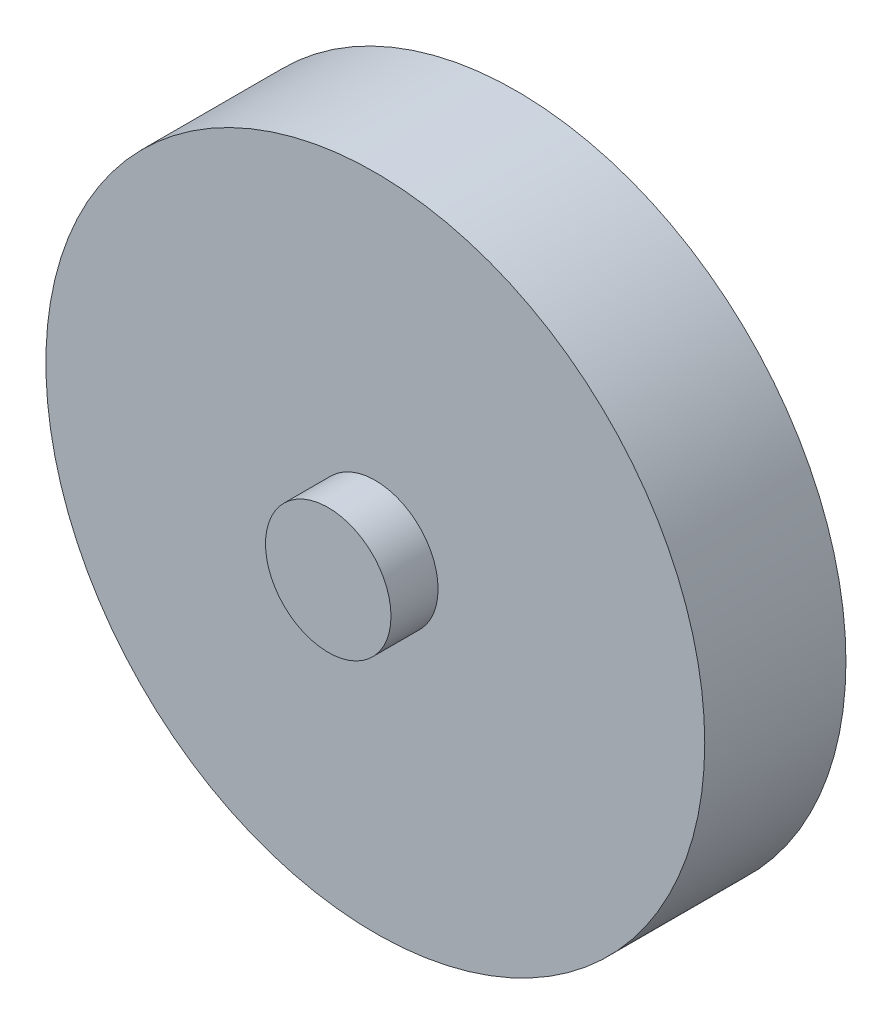
SolidWorks part; units mm, degrees
ref_plane "前视基准面" through (0, 0, 0) normal (0, 0, 1) x (1, 0, 0)
ref_plane "上视基准面" through (0, 0, 0) normal (0, 1, 0) x (1, 0, 0)
ref_plane "右视基准面" through (0, 0, 0) normal (1, 0, 0) x (0, 0, -1)
other "Configuration Table"
sketch "草图1" plane through (0, 0, 0) normal (0, 0, 1) x (1, 0, 0)
  circle A0 centre (0, 0) radius 8
extrude "凸台-拉伸1" add sketch "草图1" along normal blind 24
sketch "草图2" plane through (0, 0, 0) normal (0, 0, 1) x (1, 0, 0)
  circle A0 centre (0, 0) radius 42
extrude "凸台-拉伸2" add sketch "草图2" along normal blind 18
sketch "草图3" plane through (0, 0, 18) normal (0, 0, 1) x (1, 0, 0)
  arc A0 (4, 30) -> (-4, 30) centre (0, 30) ccw
  arc A1 (-4, 30) -> (4, 30) centre (0, 30) ccw
